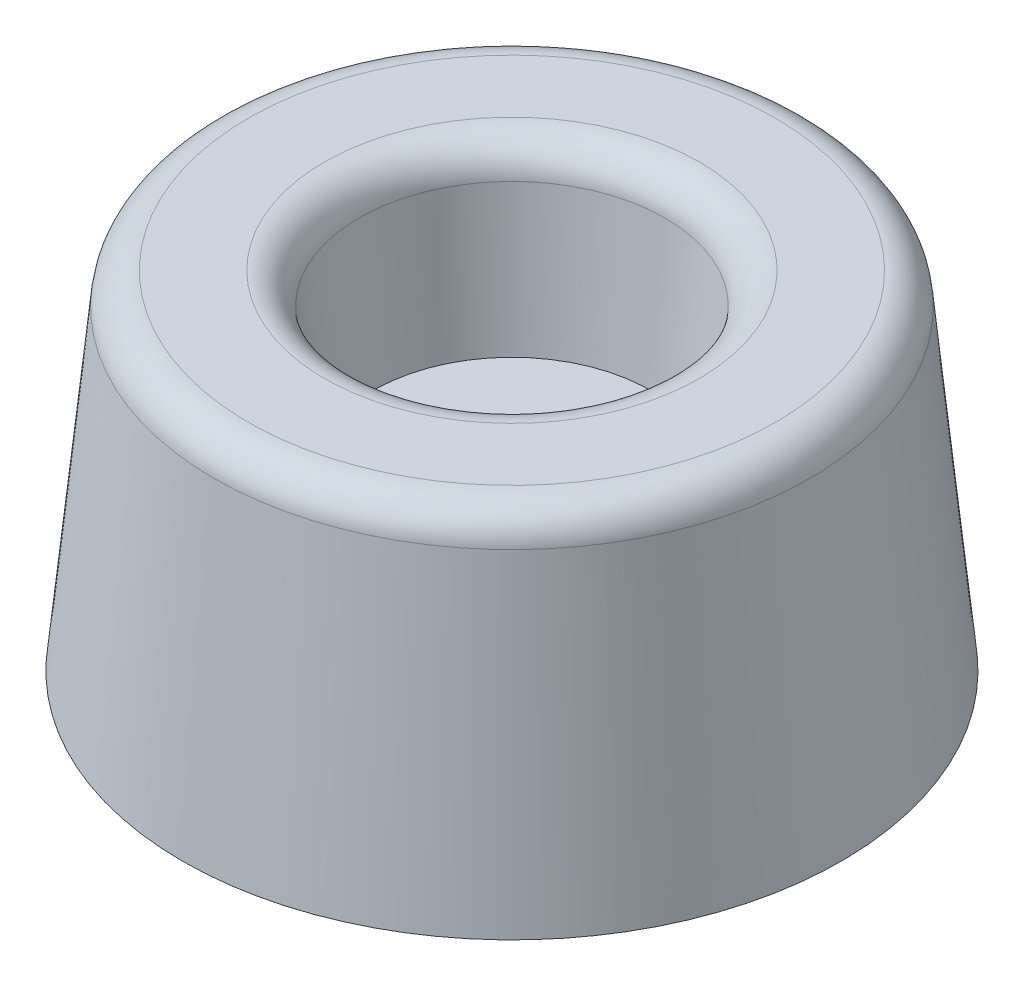
SolidWorks part; units mm, degrees
material "Glass"
ref_plane "Front Plane" through (0, 0, 0) normal (0, 0, 1) x (1, 0, 0)
ref_plane "Top Plane" through (0, 0, 0) normal (0, 1, 0) x (1, 0, 0)
ref_plane "Right Plane" through (0, 0, 0) normal (1, 0, 0) x (0, 0, -1)
sketch "Sketch1" plane through (0, 0, 0) normal (0, 0, 1) x (1, 0, 0)
  line L0 (0, 27.67) -> (0, -13.4241) construction
  line L1 (0, -55) -> (0, 55) construction
  line L2 (0, 0) -> (9.5, 0)
  line L3 (55, 0) -> (-55, 0) construction
  line L4 (9.5, 0) -> (8.5, 10)
  line L5 (8.5, 10) -> (4.5, 10)
  line L6 (4.5, 10) -> (4, 5)
  line L7 (4, 5) -> (0, 5)
  line L8 (0, 5) -> (0, 0)
  point P9 (8.1726, 10)
  point P14 (3.6805, 10)
  point P15 (2.3477, 4.824)
  dimension "D1" = 19
  dimension "D2" = 10
  dimension "D3" = 5
  dimension "D4" = 17
  dimension "D5" = 9
  dimension "D6" = 8
revolve "Revolve1" add sketch "Sketch1" angle 360 about L0
fillet "Fillet1" radius 1 2 edges at (0, 10, 8.5) (0, 10, 4.5)
